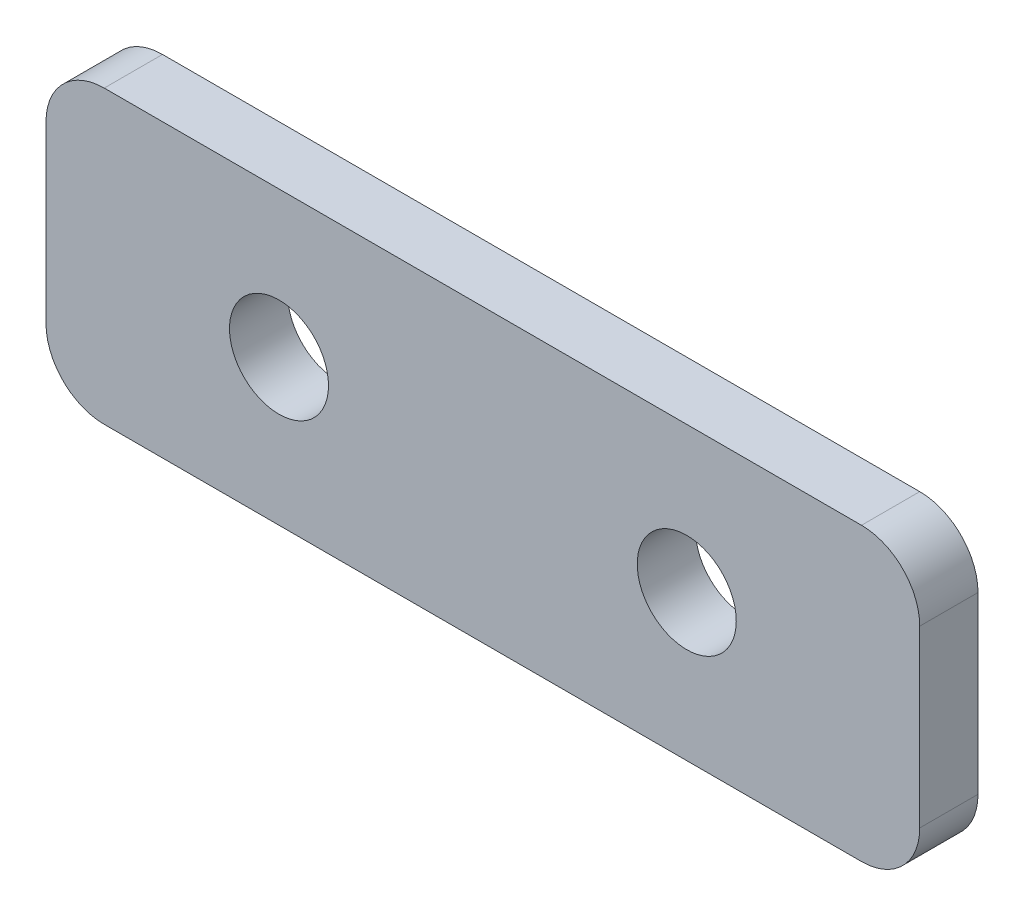
SolidWorks part; units mm, degrees
material "AISI 1020"
ref_plane "Front Plane" through (0, 0, 0) normal (0, 0, 1) x (1, 0, 0)
ref_plane "Top Plane" through (0, 0, 0) normal (0, 1, 0) x (1, 0, 0)
ref_plane "Right Plane" through (0, 0, 0) normal (1, 0, 0) x (0, 0, -1)
sketch "Sketch1" plane through (0, 0, 0) normal (0, 0, 1) x (1, 0, 0)
  line L1 (-15, -5) -> (15, -5)
  line L2 (-15, -5) -> (-15, 5)
  line L3 (-15, 5) -> (15, 5)
  line L4 (15, -5) -> (15, 5)
  line L5 (-15, -5) -> (15, 5) construction
  line L6 (-15, 5) -> (15, -5) construction
  point P0 (0, 0)
  dimension "D1" = 10
  dimension "D2" = 30
extrude "Boss-Extrude1" add sketch "Sketch1" along normal blind 2
fillet "Fillet2" radius 2 4 edges at (15, -5, 1) (15, 5, 1) (-15, 5, 1) (-15, -5, 1)
hole_wizard "M3 Clearance Hole1" positions "Sketch2" profile "Sketch3" hole size "M3" standard "ANSI Metric" end condition through all
sketch "Sketch2" plane through (0, 0, 2) normal (0, 0, 1) x (1, 0, 0)
  line L0 (13, 5) -> (-13, 5) construction
  point P0 (-7, 0)
  point P2 (7, 0)
  dimension "D1" = 7
  dimension "D2" = 7
  dimension "D3" = 5
  dimension "D4" = 5
sketch "Sketch3" plane through (-7, 0, 2) normal (1, 0, 0) x (0, -1, 0)
  line L0 (0, 0) -> (0, 2)
  line L1 (0, 2) -> (1.7, 2)
  line L2 (1.7, 2) -> (1.7, 0)
  line L5 (1.7, 0) -> (0, 0)
  line L11 (0, -6.35) -> (0, 107.95) construction
  dimension "Thru Hole Dia." = 3.4
  dimension "Thru Hole Depth" = 2
